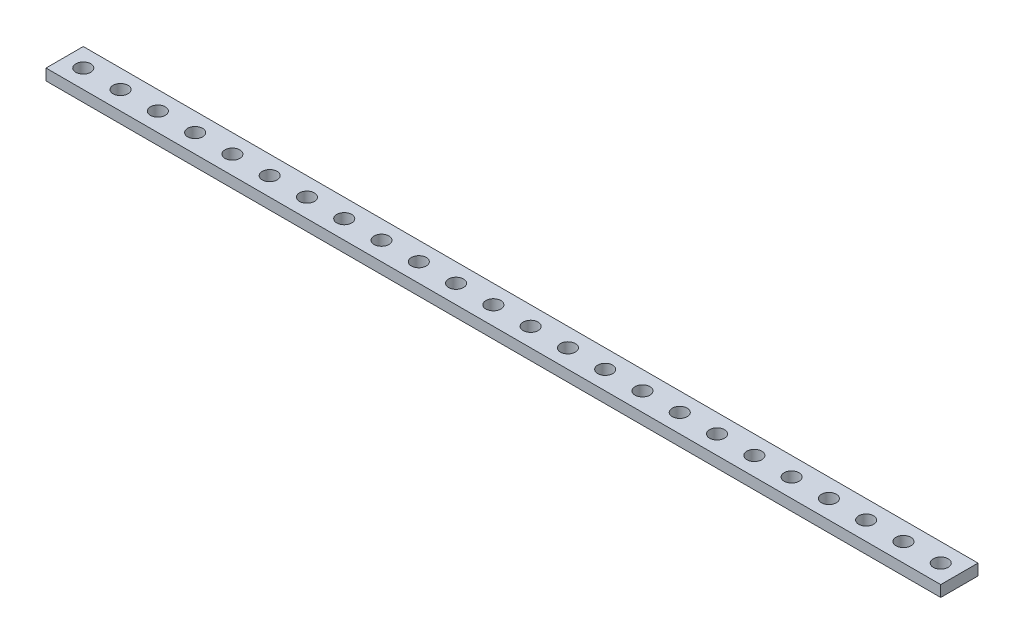
SolidWorks part; units mm, degrees
ref_plane "Plan de face" through (0, 0, 0) normal (0, 0, 1) x (1, 0, 0)
ref_plane "Plan de dessus" through (0, 0, 0) normal (0, 1, 0) x (1, 0, 0)
ref_plane "Plan de droite" through (0, 0, 0) normal (1, 0, 0) x (0, 0, -1)
sketch "Esquisse1" plane through (0, 0, 0) normal (0, 1, 0) x (1, 0, 0)
  line L0 (0, 0) -> (140, 0)
  line L1 (0, 0) -> (-140, 0)
  line L2 (-140, 0) -> (-140, 10)
  line L3 (-140, 10) -> (140, 10)
  line L4 (140, 10) -> (140, 0)
  line L5 (-140, 5) -> (-135, 5) construction
  circle A0 centre (-135, 5) radius 2
  circle A1 centre (-125, 5) radius 2
  circle A2 centre (-115, 5) radius 2
  circle A3 centre (-105, 5) radius 2
  circle A4 centre (-95, 5) radius 2
  circle A5 centre (-85, 5) radius 2
  circle A6 centre (-75, 5) radius 2
  circle A7 centre (-65, 5) radius 2
  circle A8 centre (-55, 5) radius 2
  circle A9 centre (-45, 5) radius 2
  circle A10 centre (-35, 5) radius 2
  circle A11 centre (-25, 5) radius 2
  circle A12 centre (-15, 5) radius 2
  circle A13 centre (-5, 5) radius 2
  circle A14 centre (5, 5) radius 2
  circle A15 centre (15, 5) radius 2
  circle A16 centre (25, 5) radius 2
  circle A17 centre (35, 5) radius 2
  circle A18 centre (45, 5) radius 2
  circle A19 centre (55, 5) radius 2
  circle A20 centre (65, 5) radius 2
  circle A21 centre (75, 5) radius 2
  circle A22 centre (85, 5) radius 2
  circle A23 centre (95, 5) radius 2
  circle A24 centre (105, 5) radius 2
  circle A25 centre (115, 5) radius 2
  circle A26 centre (125, 5) radius 2
  circle A27 centre (135, 5) radius 2
  dimension "D3" = 28
  dimension "D1" = 140
  dimension "D2" = 140
extrude "Boss.-Extru.1" add sketch "Esquisse1" along normal blind 3
sketch "Esquisse2" plane through (0, 3, 0) normal (0, 1, 0) x (1, 0, 0)
  line L0 (-140, 10) -> (100, 10) construction
  line L1 (140, 10) -> (-140, 10) construction
  line L2 (100, 10) -> (100, 0)
  line L3 (-140, 0) -> (140, 0) construction
  line L4 (100, 0) -> (140, 0)
  line L5 (140, 0) -> (140, 10)
  line L6 (140, 10) -> (100, 10)
extrude "Enlèv. mat.-Extru.1" cut sketch "Esquisse2" against normal up to next
